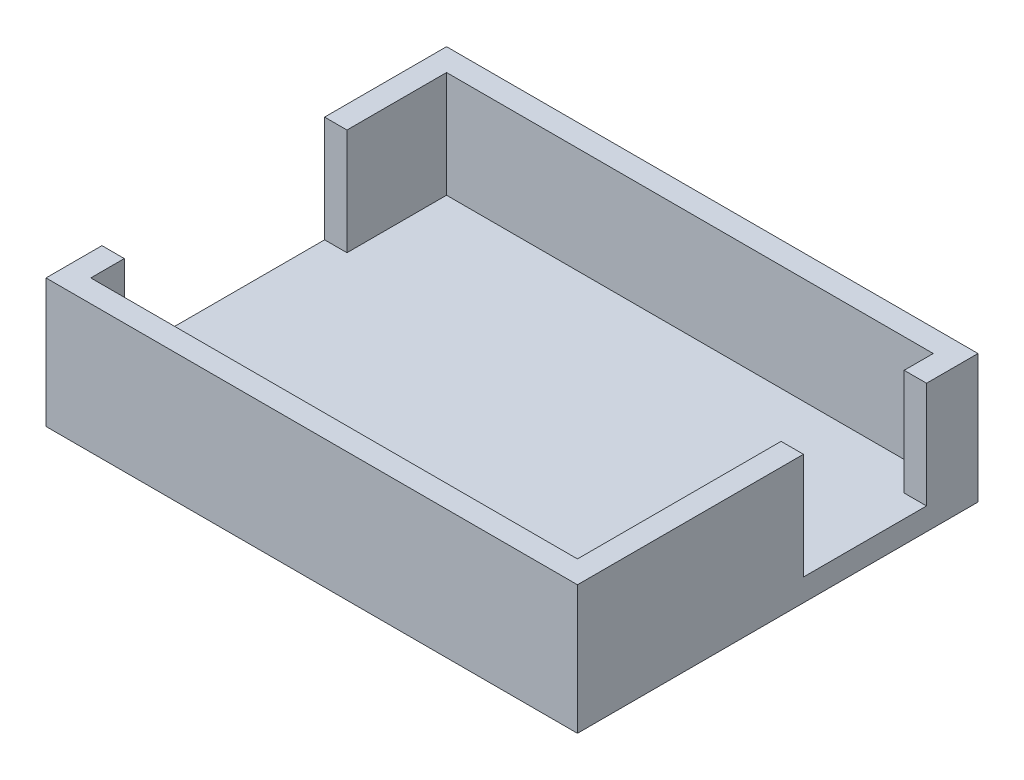
SolidWorks part; units mm, degrees
ref_plane "Plan de face" through (0, 0, 0) normal (0, 0, 1) x (1, 0, 0)
ref_plane "Plan de dessus" through (0, 0, 0) normal (0, 1, 0) x (1, 0, 0)
ref_plane "Plan de droite" through (0, 0, 0) normal (1, 0, 0) x (0, 0, -1)
sketch "Esquisse1" plane through (0, 0, 0) normal (0, 1, 0) x (1, 0, 0)
  line L1 (0, 0) -> (47.5, 0)
  line L2 (0, 0) -> (0, -35.8)
  line L3 (0, -35.8) -> (47.5, -35.8)
  line L4 (47.5, 0) -> (47.5, -35.8)
  dimension "D1" = 47.5
  dimension "D2" = 35.8
extrude "Boss.-Extru.2" add sketch "Esquisse1" along normal blind 2
sketch "Esquisse2" plane through (0, 2, 0) normal (0, 1, 0) x (1, 0, 0)
  line L0 (47.5, -35.8) -> (47.5, 0) construction
  line L1 (0, -35.8) -> (47.5, -35.8)
  line L2 (0, -35.8) -> (0, -33.8)
  line L3 (0, -33.8) -> (47.5, -33.8)
  line L4 (47.5, -35.8) -> (47.5, -33.8)
  dimension "D1" = 2
extrude "Boss.-Extru.3" add sketch "Esquisse2" along normal blind 9.5
sketch "Esquisse3" plane through (0, 2, 0) normal (0, 1, 0) x (1, 0, 0)
  line L0 (47.5, -33.8) -> (47.5, 0) construction
  line L1 (0, 0) -> (47.5, 0)
  line L2 (0, 0) -> (0, -2)
  line L3 (0, -2) -> (47.5, -2)
  line L4 (47.5, 0) -> (47.5, -2)
  dimension "D1" = 2
extrude "Boss.-Extru.4" add sketch "Esquisse3" along normal blind 9.5
sketch "Esquisse4" plane through (0, 2, 0) normal (0, 1, 0) x (1, 0, 0)
  line L1 (47.5, -2) -> (45.5, -2)
  line L2 (47.5, -2) -> (47.5, -4.6)
  line L3 (47.5, -4.6) -> (45.5, -4.6)
  line L4 (45.5, -2) -> (45.5, -4.6)
  dimension "D1" = 2.6
  dimension "D2" = 2
extrude "Boss.-Extru.5" add sketch "Esquisse4" along normal blind 9.5
sketch "Esquisse5" plane through (0, 2, 0) normal (0, 1, 0) x (1, 0, 0)
  line L0 (45.5, -4.6) -> (47.5, -4.6) construction
  line L1 (47.5, -33.8) -> (45.5, -33.8)
  line L2 (47.5, -33.8) -> (47.5, -15.6)
  line L3 (47.5, -15.6) -> (45.5, -15.6)
  line L4 (45.5, -33.8) -> (45.5, -15.6)
  dimension "D1" = 11
  dimension "D2" = 2
extrude "Boss.-Extru.6" add sketch "Esquisse5" along normal blind 9.5
sketch "Esquisse6" plane through (0, 2, 0) normal (0, 1, 0) x (1, 0, 0)
  line L1 (0, -2) -> (2, -2)
  line L2 (0, -2) -> (0, -10.9)
  line L3 (0, -10.9) -> (2, -10.9)
  line L4 (2, -2) -> (2, -10.9)
  dimension "D1" = 8.9
  dimension "D2" = 2
extrude "Boss.-Extru.7" add sketch "Esquisse6" along normal blind 9.5
sketch "Esquisse8" plane through (0, 2, 0) normal (0, 1, 0) x (1, 0, 0)
  line L1 (0, -33.8) -> (2, -33.8)
  line L2 (0, -33.8) -> (0, -30.8)
  line L3 (0, -30.8) -> (2, -30.8)
  line L4 (2, -33.8) -> (2, -30.8)
  dimension "D1" = 3
  dimension "D2" = 2
extrude "Boss.-Extru.8" add sketch "Esquisse8" along normal blind 9.5
